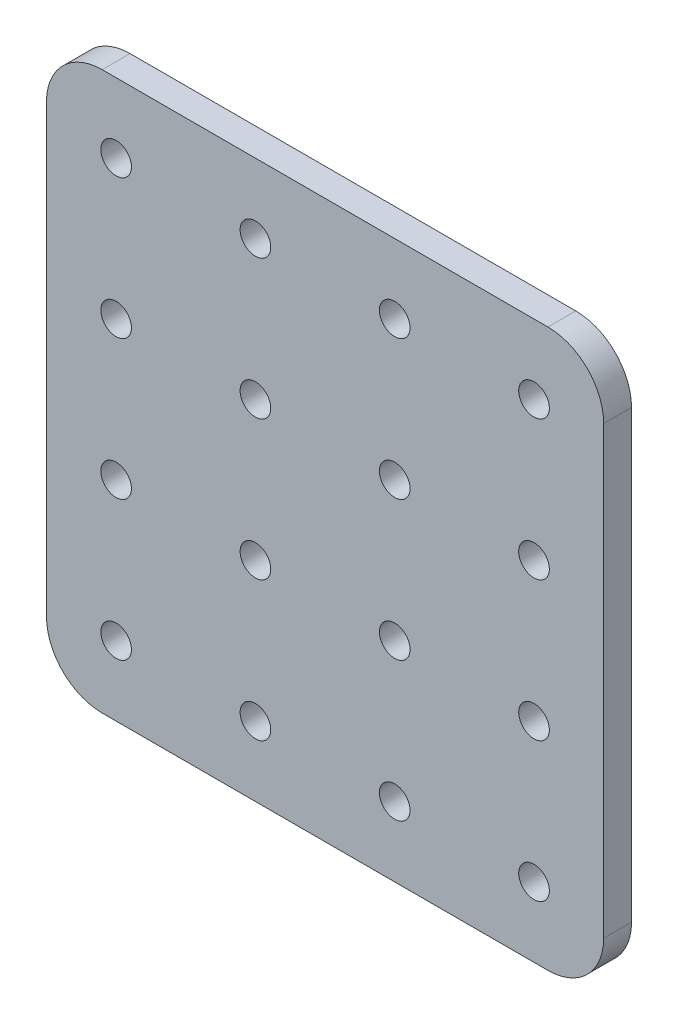
SolidWorks part; units mm, degrees
ref_plane "Front Plane" through (0, 0, 0) normal (0, 0, 1) x (1, 0, 0)
ref_plane "Top Plane" through (0, 0, 0) normal (0, 1, 0) x (1, 0, 0)
ref_plane "Right Plane" through (0, 0, 0) normal (1, 0, 0) x (0, 0, -1)
sketch "Sketch1" plane through (0, 0, 0) normal (0, 0, 1) x (1, 0, 0)
  line L0 (0, 0) -> (12.7, 0) construction
  line L1 (0, 0) -> (0, -12.7) construction
  line L3 (-6.35, 6.35) -> (44.45, 6.35)
  line L4 (-6.35, 6.35) -> (-6.35, -44.45)
  line L5 (-6.35, -44.45) -> (44.45, -44.45)
  line L6 (44.45, 6.35) -> (44.45, -44.45)
  circle A0 centre (0, 0) radius 1.397
  circle A1 centre (12.7, 0) radius 1.397
  circle A2 centre (25.4, 0) radius 1.397
  circle A3 centre (38.1, 0) radius 1.397
  circle A4 centre (12.7, -12.7) radius 1.397
  circle A5 centre (25.4, -12.7) radius 1.397
  circle A6 centre (38.1, -12.7) radius 1.397
  circle A7 centre (12.7, -25.4) radius 1.397
  circle A8 centre (25.4, -25.4) radius 1.397
  circle A9 centre (38.1, -25.4) radius 1.397
  circle A10 centre (12.7, -38.1) radius 1.397
  circle A11 centre (25.4, -38.1) radius 1.397
  circle A12 centre (38.1, -38.1) radius 1.397
  circle A13 centre (0, -12.7) radius 1.397
  circle A14 centre (0, -25.4) radius 1.397
  circle A15 centre (0, -38.1) radius 1.397
  dimension "D1" = 2.794
  dimension "D4" = 12.7
  dimension "D5" = 12.7
  dimension "D6" = 6.35
  dimension "D7" = 6.35
  dimension "D8" = 6.35
  dimension "D9" = 6.35
  dimension "D2" = 4
  dimension "D3" = 4
extrude "Boss-Extrude1" add sketch "Sketch1" along normal blind 2.54
fillet "Fillet1" radius 5.08 4 edges at (-6.35, -44.45, 1.27) (44.45, -44.45, 1.27) (44.45, 6.35, 1.27) (-6.35, 6.35, 1.27)
